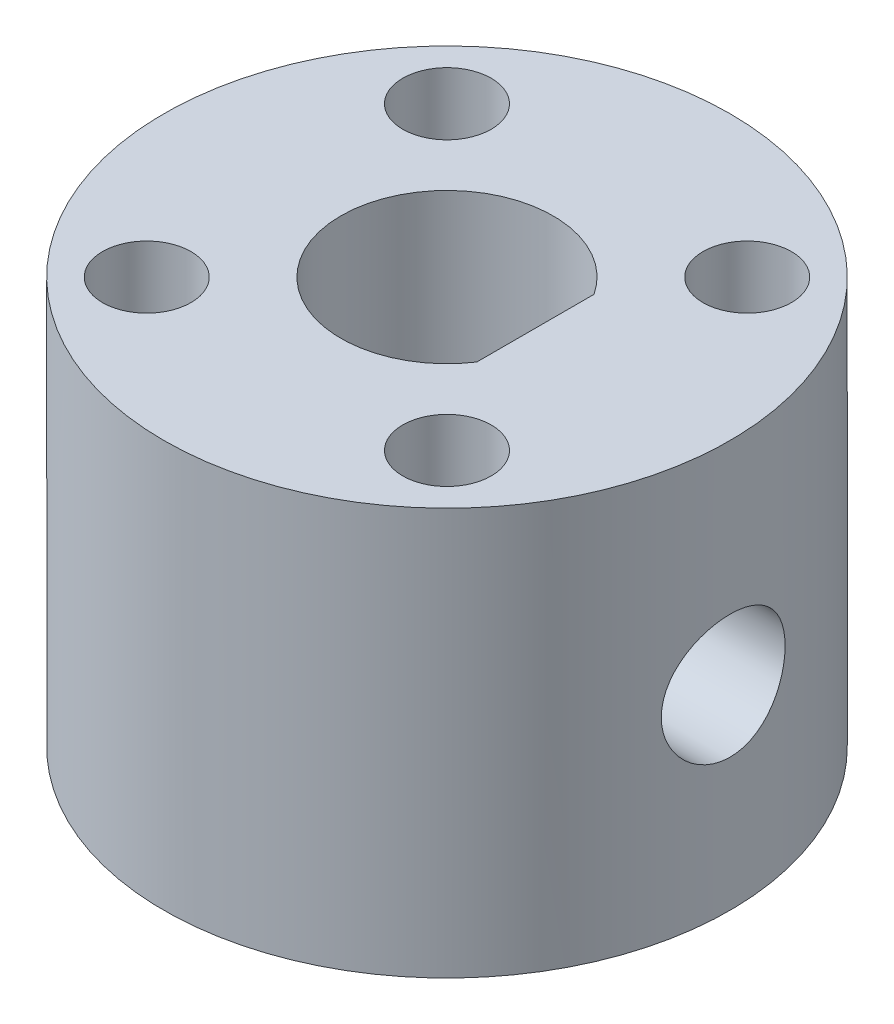
SolidWorks part; units mm, degrees
ref_plane "前视基准面" through (0, 0, 0) normal (0, 0, 1) x (1, 0, 0)
ref_plane "上视基准面" through (0, 0, 0) normal (0, 1, 0) x (1, 0, 0)
ref_plane "右视基准面" through (0, 0, 0) normal (1, 0, 0) x (0, 0, -1)
sketch "草图1" plane through (0, 0, 0) normal (0, 1, 0) x (1, 0, 0)
  line L0 (2.5, 1.6583) -> (2.5, -1.6583)
  line L1 (2.55, 1.6733) -> (2.55, -1.6733) construction
  line L2 (0, 0) -> (4.2426, 4.2426) construction
  arc A0 (2.5, 1.6583) -> (2.5, -1.6583) centre (0, 0) ccw
  circle A1 centre (0, 0) radius 6 construction
  circle A2 centre (4.2426, 4.2426) radius 1.25
  circle A3 centre (4.2426, -4.2426) radius 1.25
  circle A4 centre (-4.2426, -4.2426) radius 1.25
  circle A5 centre (-4.2426, 4.2426) radius 1.25
  circle A6 centre (0, 0) radius 8
  arc A7 (2.55, 1.6733) -> (2.55, -1.6733) centre (0, 0) ccw construction
  point P15 (0, 0)
  point P20 (0, 0)
  dimension "D1" = 6
  dimension "D2" = 12
  dimension "D3" = 2.5
  dimension "D5" = 16
  dimension "D6" = 2.5
  dimension "D7" = 0.05
  dimension "D4" = 4
extrude "凸台-拉伸1" add sketch "草图1" along normal blind 12.5
cosmetic thread "装饰螺纹线2" parameters "D2"=3
cosmetic thread "装饰螺纹线3" parameters "D2"=3
cosmetic thread "装饰螺纹线4" parameters "D2"=3
cosmetic thread "装饰螺纹线5" parameters "D2"=3
sketch "草图3" plane through (2.5, 0, 0) normal (-1, 0, 0) x (0, 0, 1)
  line L0 (5.4926, 12.5) -> (2.9926, 12.5) construction
  circle A0 centre (0, 6.5) radius 1.75
  dimension "D1" = 3.5
  dimension "D2" = 6
extrude "切除-拉伸1" cut sketch "草图3" against normal blind 10
cosmetic thread "装饰螺纹线1" parameters "D2"=5
sketch "草图5" plane through (0, 0, 0) normal (0, -1, 0) x (1, 0, 0)
  circle A0 centre (0, 0) radius 11.0856
extrude "切除-拉伸2" cut sketch "草图5" against normal blind 1
